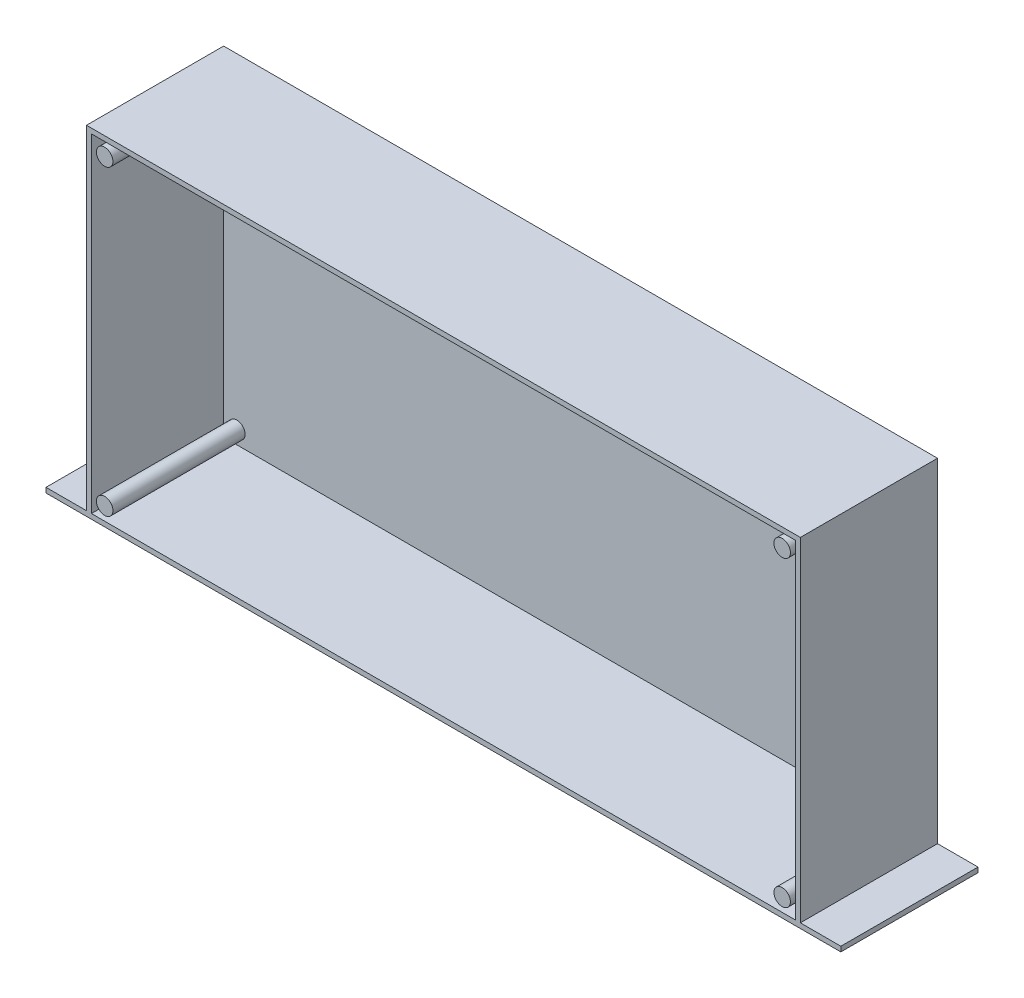
SolidWorks part; units mm, degrees
material "PBT General Purpose"
ref_plane "Front Plane" through (0, 0, 0) normal (0, 0, 1) x (1, 0, 0)
ref_plane "Top Plane" through (0, 0, 0) normal (0, 1, 0) x (1, 0, 0)
ref_plane "Right Plane" through (0, 0, 0) normal (1, 0, 0) x (0, 0, -1)
sketch "Sketch1" plane through (0, 0, 0) normal (0, 0, 1) x (1, 0, 0)
  line L0 (0, 0) -> (-24.5, 0)
  line L1 (0, 0) -> (432, 0)
  line L2 (0, 3) -> (0, 205)
  line L3 (0, 205) -> (432, 205)
  line L4 (432, 3) -> (432, 205)
  line L5 (-24.5, 0) -> (-24.5, 3)
  line L6 (-24.5, 3) -> (0, 3)
  line L7 (216, 205) -> (216, 0) construction
  line L8 (432, 0) -> (456.5, 0)
  line L9 (456.5, 3) -> (432, 3)
  line L10 (456.5, 0) -> (456.5, 3)
  dimension "D1" = 432
  dimension "D2" = 205
  dimension "D3" = 240.5
  dimension "D4" = 3
extrude "Boss-Extrude1" add sketch "Sketch1" along normal blind 3
sketch "Sketch2" plane through (0, 0, 3) normal (0, 0, 1) x (1, 0, 0)
  line L3 (3, 3) -> (429, 3)
  line L6 (429, 3) -> (429, 202)
  line L7 (429, 202) -> (3, 202)
  line L8 (3, 202) -> (3, 3)
  line L9 (429, 3) -> (429, 202)
  line L10 (429, 202) -> (3, 202)
  line L11 (3, 202) -> (3, 3)
  line L18 (432, 205) -> (0, 205) construction
  line L19 (432, 205) -> (0, 205)
  line L22 (456.5, 0) -> (456.5, 3) construction
  line L23 (456.5, 3) -> (432, 3) construction
  line L24 (432, 3) -> (432, 205) construction
  line L25 (0, 205) -> (0, 3) construction
  line L26 (0, 3) -> (-24.5, 3) construction
  line L27 (-24.5, 3) -> (-24.5, 0) construction
  line L28 (456.5, 0) -> (456.5, 3)
  line L29 (456.5, 3) -> (432, 3)
  line L30 (432, 3) -> (432, 205)
  line L31 (0, 205) -> (0, 3)
  line L32 (0, 3) -> (-24.5, 3)
  line L33 (-24.5, 3) -> (-24.5, 0)
  line L34 (-24.5, 0) -> (456.5, 0) construction
  line L35 (-24.5, 0) -> (456.5, 0)
  dimension "D1" = 3
extrude "Boss-Extrude2" add sketch "Sketch2" along normal blind 80
sketch "Sketch3" plane through (0, 0, 3) normal (0, 0, 1) x (1, 0, 0)
  line L0 (11, 194) -> (421, 194) construction
  line L1 (421, 194) -> (421, 11) construction
  line L2 (429, 202) -> (3, 202) construction
  line L3 (429, 3) -> (429, 202) construction
  line L4 (11, 194) -> (11, 11) construction
  line L5 (11, 11) -> (421, 11) construction
  line L6 (3, 202) -> (3, 3) construction
  line L7 (3, 3) -> (429, 3) construction
  circle A0 centre (11, 194) radius 5
  circle A1 centre (421, 194) radius 5
  circle A2 centre (421, 11) radius 5
  circle A3 centre (11, 11) radius 5
  dimension "D5" = 10
  dimension "D6" = 10
  dimension "D7" = 10
  dimension "D8" = 10
  dimension "D1" = 8
  dimension "D2" = 8
  dimension "D3" = 8
  dimension "D4" = 8
extrude "Boss-Extrude3" add sketch "Sketch3" along normal blind 80
